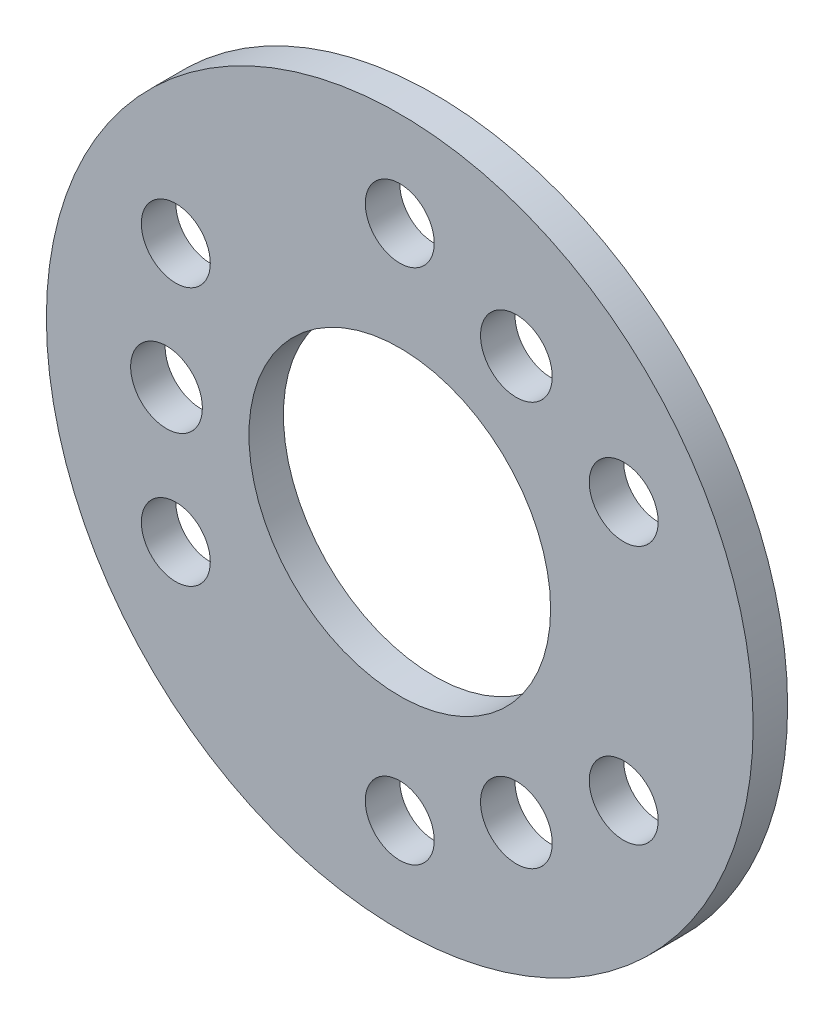
SolidWorks part; units mm, degrees
ref_plane "前视基准面" through (0, 0, 0) normal (0, 0, 1) x (1, 0, 0)
ref_plane "上视基准面" through (0, 0, 0) normal (0, 1, 0) x (1, 0, 0)
ref_plane "右视基准面" through (0, 0, 0) normal (1, 0, 0) x (0, 0, -1)
sketch "草图1" plane through (0, 0, 0) normal (0, 0, 1) x (1, 0, 0)
  line L0 (-0.9852, 0.129) -> (-0.9852, -3.2208) construction
  circle A0 centre (-0.9852, 0.129) radius 15 construction
  circle A1 centre (-0.9852, 0.129) radius 13.53 construction
  circle A2 centre (-0.9852, -14.871) radius 2
  circle A3 centre (-13.9756, -7.371) radius 2
  circle A4 centre (-13.9756, 7.629) radius 2
  circle A5 centre (-0.9852, 15.129) radius 2
  circle A6 centre (12.0052, 7.629) radius 2
  circle A7 centre (12.0052, -7.371) radius 2
  circle A8 centre (-14.5152, 0.129) radius 2.08
  circle A9 centre (5.7798, 11.8463) radius 2.08
  circle A10 centre (5.7798, -11.5883) radius 2.08
  circle A11 centre (-0.9852, 0.129) radius 8.75
  circle A12 centre (-0.9852, 0.129) radius 20.5
extrude "凸台-拉伸1" add sketch "草图1" along normal blind 2 contours A12
sketch "草图2" plane through (0, 0, 0) normal (0, 0, -1) x (-1, 0, 0)
  line L0 (0.9852, 0.129) -> (0.9852, -8.621) construction
  circle A0 centre (0.9852, 0.129) radius 8.75 construction
sketch "草图3" plane through (0, 0, 0) normal (0, 0, -1) x (-1, 0, 0)
  circle A0 centre (0.9852, 0.129) radius 5
sketch "草图4" plane through (0, 0, 2) normal (0, 0, 1) x (1, 0, 0)
  circle A1 centre (-0.9852, 0.129) radius 5
